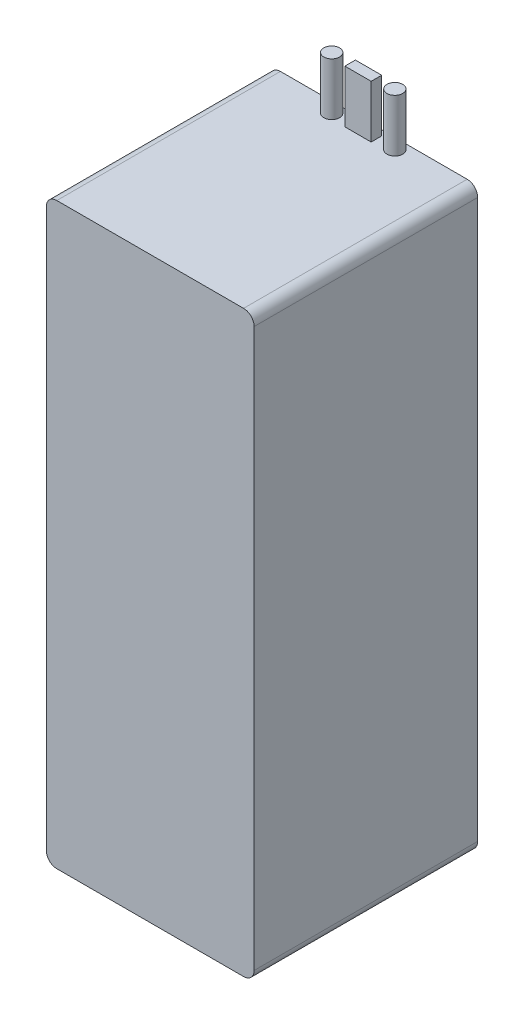
SolidWorks part; units mm, degrees
ref_plane "Front" through (0, 0, 0) normal (0, 0, 1) x (1, 0, 0)
ref_plane "Top" through (0, 0, 0) normal (0, 1, 0) x (1, 0, 0)
ref_plane "Right" through (0, 0, 0) normal (1, 0, 0) x (0, 0, -1)
sketch "Sketch1" plane through (0, 0, 0) normal (0, 1, 0) x (1, 0, 0)
  line L1 (-19.75, -21.25) -> (19.75, -21.25)
  line L2 (-19.75, -21.25) -> (-19.75, 21.25)
  line L3 (-19.75, 21.25) -> (19.75, 21.25)
  line L4 (19.75, -21.25) -> (19.75, 21.25)
  line L5 (-19.75, -21.25) -> (19.75, 21.25) construction
  line L6 (-19.75, 21.25) -> (19.75, -21.25) construction
  point P0 (0, 0)
  dimension "D1" = 39.5
  dimension "D2" = 42.5
extrude "Boss-Extrude1" add sketch "Sketch1" along normal blind 110
sketch "Sketch2" plane through (0, 110, 0) normal (0, 1, 0) x (1, 0, 0)
  line L0 (-19.75, 19.25) -> (19.75, 19.25) construction
  line L1 (-19.75, 21.25) -> (-19.75, -21.25) construction
  line L2 (19.75, -21.25) -> (19.75, 21.25) construction
  line L3 (19.75, 21.25) -> (-19.75, 21.25) construction
  line L4 (0, 21.25) -> (0, 1.3075) construction
  line L6 (-2.5, 20.25) -> (2.5, 20.25)
  line L7 (-2.5, 20.25) -> (-2.5, 18.25)
  line L8 (-2.5, 18.25) -> (2.5, 18.25)
  line L9 (2.5, 20.25) -> (2.5, 18.25)
  line L10 (-2.5, 20.25) -> (2.5, 18.25) construction
  line L11 (-2.5, 18.25) -> (2.5, 20.25) construction
  circle A0 centre (-6, 19.25) radius 1.5
  circle A2 centre (6, 19.25) radius 1.5
  point P14 (0, 19.25)
  dimension "D2" = 3
  dimension "D3" = 3
  dimension "D6" = 6
  dimension "D1" = 2
  dimension "D4" = 5
  dimension "D5" = 2
  dimension "D7" = 6
extrude "Boss-Extrude2" add sketch "Sketch2" along normal blind 10
fillet "Fillet1" radius 2 4 edges at (19.75, 110, 0) (-19.75, 110, 0) (19.75, 0, 0) (-19.75, 0, 0)
